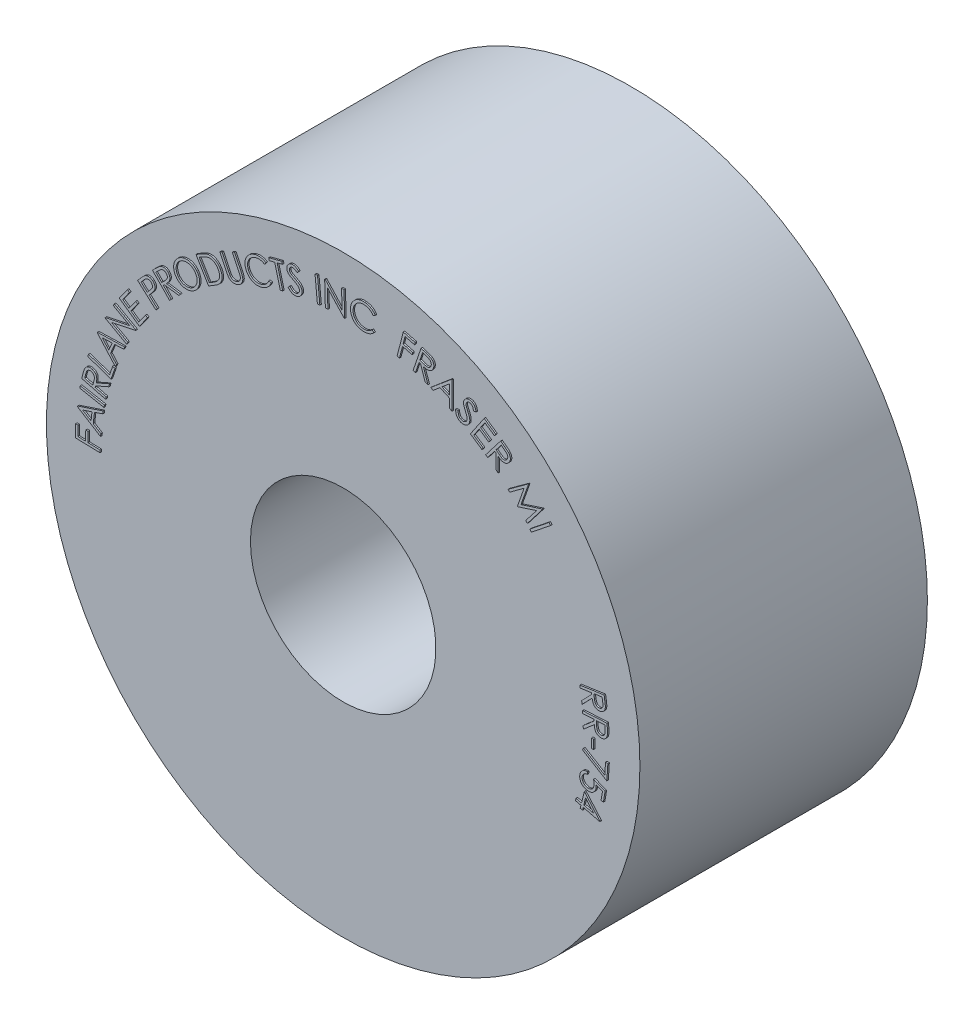
SolidWorks part; units mm, degrees
ref_plane "Front" through (0, 0, 0) normal (0, 0, 1) x (1, 0, 0)
ref_plane "Top" through (0, 0, 0) normal (0, 1, 0) x (1, 0, 0)
ref_plane "Right" through (0, 0, 0) normal (1, 0, 0) x (0, 0, -1)
sketch "Sketch1" plane through (0, 0, 0) normal (0, 0, 1) x (1, 0, 0)
  circle A0 centre (0, 0) radius 50.8
  dimension "D1" = 101.6
extrude "Base-Extrude" add sketch "Sketch1" against normal blind 49.2125
sketch "Sketch2" plane through (0, 0, -49.2125) normal (0, 0, -1) x (-1, 0, 0)
  circle A0 centre (0, 0) radius 15.875
  dimension "D1" = 31.75
extrude "Cut-Extrude1" cut sketch "Sketch2" against normal through all
sketch "Sketch3" plane through (0, 0, -49.2125) normal (0, 0, -1) x (-1, 0, 0)
  circle A0 centre (0, 0) radius 41.3957
  dimension "D1" = 82.7913
sketch "Sketch5" plane through (0, 0, 0) normal (0, 0, -1) x (-1, 0, 0)
  text T0 "FAIRLANE PRODUCTS INC  FRASER MI            RR-754" font "Century Gothic" height in points 16
extrude "Lettering" add sketch "Sketch5" against normal blind 0.254 separate body
